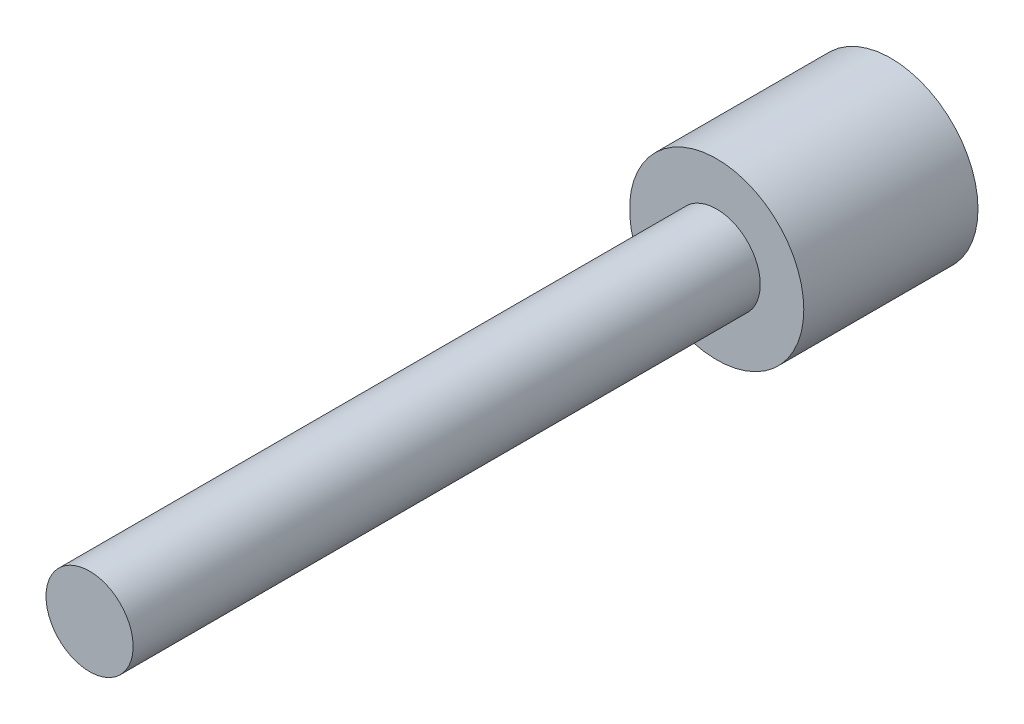
SolidWorks part; units mm, degrees
ref_plane "Plan1" through (0, 0, 0) normal (0, 0, 1) x (1, 0, 0)
ref_plane "Plan2" through (0, 0, 0) normal (0, 1, 0) x (1, 0, 0)
ref_plane "Plan3" through (0, 0, 0) normal (1, 0, 0) x (0, 0, -1)
sketch "Esquisse1" plane through (0, 0, 0) normal (0, 0, 1) x (1, 0, 0)
  circle A0 centre (0, 0) radius 5
  dimension "D1" = 10
extrude "Base-Extrusion" add sketch "Esquisse1" along normal blind 10
sketch "Esquisse2" plane through (0, 0, 0) normal (0, 0, -1) x (-1, 0, 0)
  circle A0 centre (0, 0) radius 2.5
  dimension "D1" = 5
extrude "Boss.-Extru.1" add sketch "Esquisse2" against normal blind 46
hole_wizard "Perçage1" positions "Esquisse4" profile "Esquisse3" legacy
sketch "Esquisse4" plane through (0, 0, 0) normal (0, 0, -1) x (-1, 0, 0)
  point P0 (0, 0)
sketch "Esquisse3" plane through (0, 0, 0) normal (1, 0, 0) x (0, 1, 0)
  line L0 (0, 0) -> (0, 8.5022)
  line L1 (0, 8.5022) -> (2.5, 7)
  line L2 (2.5, 7) -> (2.5, 0)
  line L4 (2.5, 0) -> (0, 0)
  line L6 (0, 8.5022) -> (-2.5, 7) construction
  line L7 (0, -4.2442) -> (0, 117.3081) construction
  dimension "Diamètre" = 5
  dimension "Profondeur" = 7
  dimension "Angle" = 118
sketch "Esquisse5" plane through (0, 0, 0) normal (0, 0, -1) x (-1, 0, 0)
  line L0 (4.3492, 2.4667) -> (6.1176, 2.4667)
  line L1 (6.1176, 2.4667) -> (6.1176, -2.2265)
  line L2 (6.1176, -2.2265) -> (4.4769, -2.2265)
  arc A0 (4.4769, -2.2265) -> (4.3492, 2.4667) centre (0, 0) ccw
extrude "Boss.-Extru.2" add sketch "Esquisse5" against normal blind 5
sketch "Esquisse8" plane through (0, 0, 0) normal (0, 0, -1) x (-1, 0, 0)
  line L0 (4.119, 2.8344) -> (6.6343, 2.8344)
  line L1 (6.6343, 2.8344) -> (6.6343, -2.731)
  line L2 (6.6343, -2.731) -> (4.1882, -2.731)
  arc A0 (4.1882, -2.731) -> (4.119, 2.8344) centre (0, 0) ccw
  dimension "D1" = 10
extrude "Enlèv. mat.-Extru.1" cut sketch "Esquisse8" against normal through all
